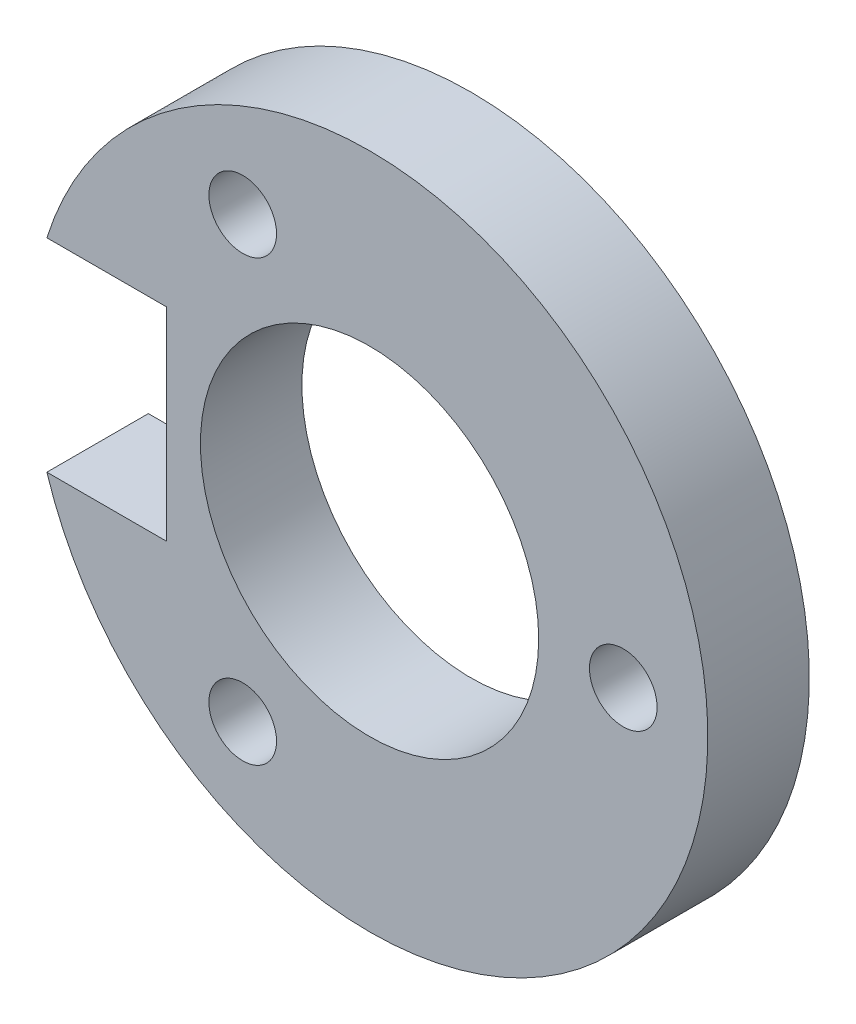
SolidWorks part; units mm, degrees
material "Acrílico (Impacto medio-alto)"
ref_plane "Alzado" through (0, 0, 0) normal (0, 0, 1) x (1, 0, 0)
ref_plane "Planta" through (0, 0, 0) normal (0, 1, 0) x (1, 0, 0)
ref_plane "Vista lateral" through (0, 0, 0) normal (1, 0, 0) x (0, 0, -1)
sketch "Croquis1" plane through (0, 0, 0) normal (0, 0, 1) x (1, 0, 0)
  line L1 (-14, 3) -> (-6, 3)
  line L2 (-14, 3) -> (-14, -3)
  line L3 (-14, -3) -> (-6, -3)
  line L4 (-6, 3) -> (-6, -3)
  line L5 (-14, 3) -> (-6, -3) construction
  line L6 (-14, -3) -> (-6, 3) construction
  line L7 (7.5, 0) -> (-3.75, 6.4952)
  line L8 (-3.75, 6.4952) -> (-3.75, -6.4952)
  line L9 (-3.75, -6.4952) -> (7.5, 0)
  circle A0 centre (0, 0) radius 10
  circle A1 centre (0, 0) radius 5
  circle A2 centre (0, 0) radius 7.5
  circle A7 centre (0, 0) radius 3.75 construction
  circle A8 centre (-3.75, 6.4952) radius 1
  circle A9 centre (7.5, 0) radius 1
  circle A10 centre (-3.75, -6.4952) radius 1
  point P5 (-10, 0)
  dimension "D1" = 20
  dimension "D2" = 10
  dimension "D3" = 2.5
  dimension "D4" = 8
  dimension "D5" = 6
  dimension "D6" = 2
  dimension "D7" = 2
  dimension "D8" = 2
extrude "Saliente-Extruir1" add sketch "Croquis1" along normal blind 3
